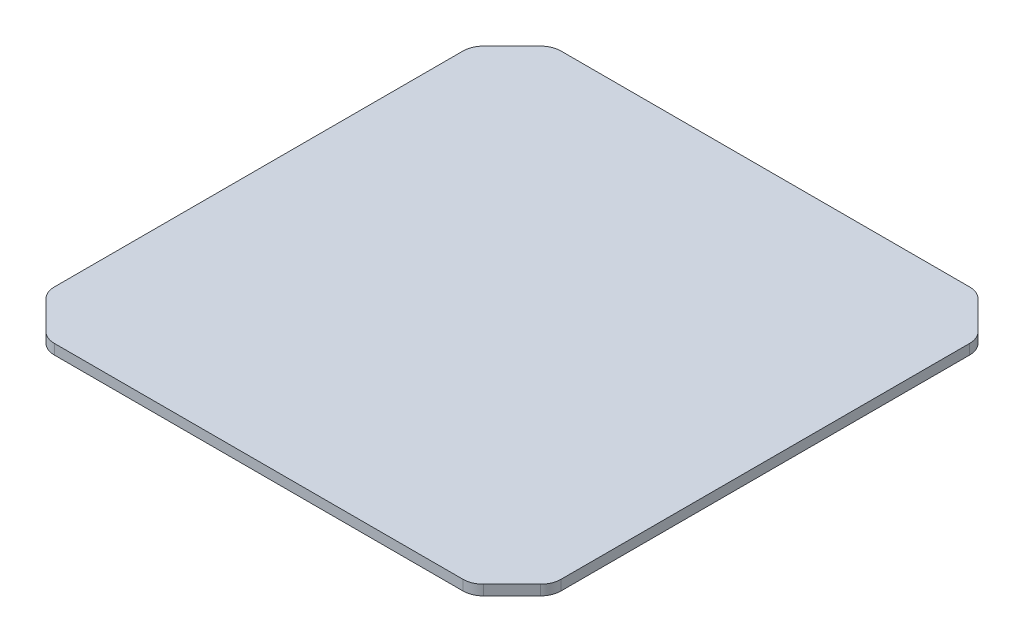
SolidWorks part; units mm, degrees
material "Acrílico (Impacto medio-alto)"
ref_plane "Alzado" through (0, 0, 0) normal (0, 0, 1) x (1, 0, 0)
ref_plane "Planta" through (0, 0, 0) normal (0, 1, 0) x (1, 0, 0)
ref_plane "Vista lateral" through (0, 0, 0) normal (1, 0, 0) x (0, 0, -1)
sketch "Sketch1" plane through (0, 0, 0) normal (0, 1, 0) x (1, 0, 0)
  line L1 (-125, -125) -> (125, -125)
  line L2 (-125, -125) -> (-125, 125)
  line L3 (-125, 125) -> (125, 125)
  line L4 (125, -125) -> (125, 125)
  line L5 (-125, -125) -> (125, 125) construction
  line L6 (-125, 125) -> (125, -125) construction
  point P0 (0, 0)
  dimension "D1" = 250
  dimension "D2" = 250
extrude "Boss-Extrude1" add sketch "Sketch1" along normal blind 5
chamfer "Chamfer1" distance 20 angle 45 4 edges at (125, 2.5, -125) (125, 2.5, 125) (-125, 2.5, 125) (-125, 2.5, -125)
fillet "Fillet2" radius 10 8 edges at (125, 2.5, -105) (105, 2.5, -125) (-125, 2.5, -105) (-105, 2.5, -125) (105, 2.5, 125) (125, 2.5, 105) (-125, 2.5, 105) (-105, 2.5, 125)
